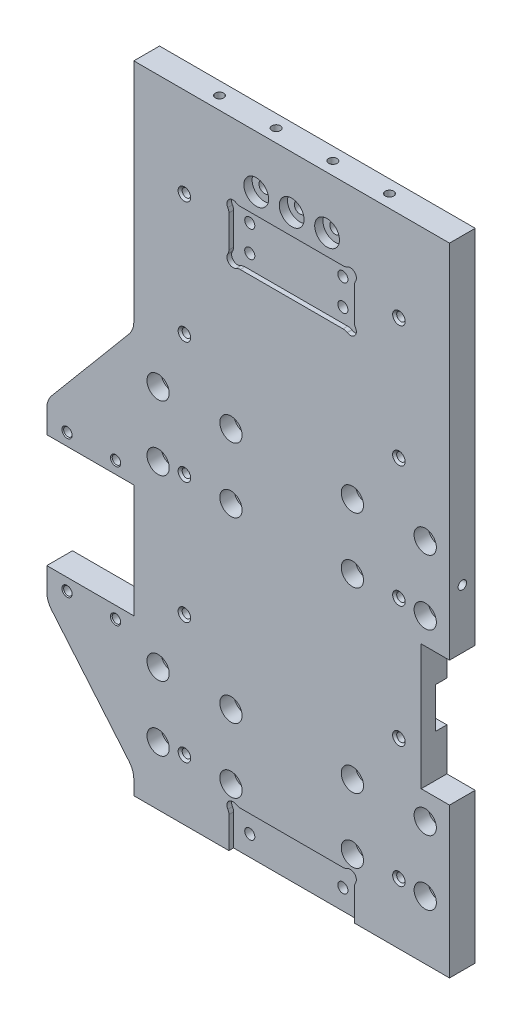
SolidWorks part; units mm, degrees
ref_plane "Front Plane" through (0, 0, 0) normal (0, 0, 1) x (1, 0, 0)
ref_plane "Top Plane" through (0, 0, 0) normal (0, 1, 0) x (1, 0, 0)
ref_plane "Right Plane" through (0, 0, 0) normal (1, 0, 0) x (0, 0, -1)
sketch "Sketch1" plane through (0, 0, 0) normal (0, 0, 1) x (1, 0, 0)
  line L0 (0, -105) -> (0, 209.5) construction
  line L1 (-78, 209.5) -> (78, 209.5)
  line L2 (-78, 209.5) -> (-78, -105)
  line L3 (-78, -105) -> (78, -105)
  line L4 (78, 209.5) -> (78, -105)
  line L5 (-78, 60) -> (78, 60) construction
  line L6 (-78, -60) -> (78, -60) construction
  line L7 (-78, 0) -> (78, 0) construction
  line L8 (30, -44) -> (66, -44) construction
  line L9 (30, -44) -> (30, -76) construction
  line L10 (30, -76) -> (66, -76) construction
  line L11 (66, -44) -> (66, -76) construction
  line L12 (30, -44) -> (66, -76) construction
  line L13 (30, -76) -> (66, -44) construction
  circle A0 centre (30, -44) radius 2.55
  circle A1 centre (66, -44) radius 2.55
  circle A2 centre (30, -76) radius 2.55
  circle A3 centre (66, -76) radius 2.55
  circle A4 centre (-66, -44) radius 2.55
  circle A5 centre (-66, -76) radius 2.55
  circle A6 centre (-30, -76) radius 2.55
  circle A7 centre (-30, -44) radius 2.55
  circle A8 centre (66, 76) radius 2.55
  circle A9 centre (66, 44) radius 2.55
  circle A10 centre (30, 76) radius 2.55
  circle A11 centre (30, 44) radius 2.55
  circle A12 centre (-30, 76) radius 2.55
  circle A13 centre (-30, 44) radius 2.55
  circle A14 centre (-66, 76) radius 2.55
  circle A15 centre (-66, 44) radius 2.55
  point P11 (48, -60)
  dimension "D3" = 5.1
  dimension "D1" = 120
  dimension "D2" = 30
  dimension "D4" = 36
  dimension "D5" = 32
  dimension "D6" = 48
  dimension "D7" = 45
  dimension "D8" = 314.5
extrude "Boss-Extrude1" add sketch "Sketch1" along normal blind 12.7
sketch "Sketch2" plane through (0, 0, 12.7) normal (0, 0, 1) x (1, 0, 0)
  circle A0 centre (-66, 76) radius 5.5
  circle A1 centre (-30, 76) radius 5.5
  circle A2 centre (-66, 44) radius 5.5
  circle A3 centre (-30, 44) radius 5.5
  circle A4 centre (30, 76) radius 5.5
  circle A5 centre (66, 76) radius 5.5
  circle A6 centre (30, 44) radius 5.5
  circle A7 centre (66, 44) radius 5.5
  circle A12 centre (-66, -44) radius 5.5
  circle A13 centre (-30, -44) radius 5.5
  circle A14 centre (-66, -76) radius 5.5
  circle A15 centre (-30, -76) radius 5.5
  circle A16 centre (30, -76) radius 5.5
  circle A17 centre (30, -44) radius 5.5
  circle A18 centre (66, -44) radius 5.5
  circle A19 centre (66, -76) radius 5.5
  dimension "D1" = 11
extrude "Cut-Extrude1" cut sketch "Sketch2" against normal blind 7
sketch "Sketch3" plane through (0, 0, 12.7) normal (0, 0, 1) x (1, 0, 0)
  line L0 (53, 209.5) -> (53, -105) construction
  line L1 (78, 209.5) -> (-78, 209.5) construction
  line L2 (-78, -105) -> (78, -105) construction
  line L3 (0, 209.5) -> (0, -105) construction
  point P8 (53, 165)
  point P9 (53, 105)
  point P11 (53, 45)
  point P12 (53, -15)
  point P13 (53, -75)
  point P14 (-53, -75)
  point P15 (-53, -15)
  point P16 (-53, 45)
  point P17 (-53, 105)
  point P18 (-53, 165)
  dimension "D1" = 53
  dimension "D2" = 30
  dimension "D4" = 60
  dimension "D3" = 5
hole_wizard "M5x0.8 Tapped Hole5" positions "3DSketch1" profile "Sketch4" tap size "M5x0.8" standard "ANSI Metric" end condition through all
sketch3d "3DSketch1"
  point P0 (53, 165, 12.7)
  point P3 (53, 105, 12.7)
  point P6 (53, 45, 12.7)
  point P9 (53, -15, 12.7)
  point P12 (53, -75, 12.7)
  point P15 (-53, 165, 12.7)
  point P18 (-53, 105, 12.7)
  point P21 (-53, 45, 12.7)
  point P24 (-53, -15, 12.7)
  point P27 (-53, -75, 12.7)
sketch "Sketch4" plane through (53, 165, 12.7) normal (1, 0, 0) x (0, -1, 0)
  line L0 (0, 0) -> (0, 12.7)
  line L1 (0, 12.7) -> (2.1, 12.7)
  line L2 (2.1, 12.7) -> (2.1, 0)
  line L5 (2.1, 0) -> (0, 0)
  line L11 (0, -6.35) -> (0, 107.95) construction
  dimension "Thru Tap Drill Dia." = 4.2
  dimension "Thru Tap Drill Depth" = 12.7
cosmetic thread "Hole Thread1" parameters "D2"=5
cosmetic thread "Hole Thread2" parameters "D2"=5
cosmetic thread "Hole Thread3" parameters "D2"=5
cosmetic thread "Hole Thread4" parameters "D2"=5
cosmetic thread "Hole Thread5" parameters "D2"=5
cosmetic thread "Hole Thread6" parameters "D2"=5
cosmetic thread "Hole Thread7" parameters "D2"=5
cosmetic thread "Hole Thread8" parameters "D2"=5
cosmetic thread "Hole Thread9" parameters "D2"=5
cosmetic thread "Hole Thread10" parameters "D2"=5
chamfer "Chamfer1" distance 1 angle 45 10 edges at (-50.9, 165, 12.7) (-50.9, 105, 12.7) (-50.9, 45, 12.7) (-50.9, -15, 12.7) (-50.9, -75, 12.7) (55.1, -75, 12.7) (55.1, -15, 12.7) (55.1, 45, 12.7) (55.1, 105, 12.7) (55.1, 165, 12.7)
sketch "Sketch5" plane through (0, 209.5, 0) normal (0, 1, 0) x (1, 0, 0)
  line L0 (0, 0) -> (0, -12.7) construction
  line L3 (78, -12.7) -> (-78, -12.7) construction
  line L5 (-42, -6.35) -> (42, -6.35) construction
  point P4 (14, -6.35)
  point P7 (0, -6.35)
  point P8 (-14, -6.35)
  dimension "D2" = 28
  dimension "D1" = 84
  dimension "D3" = 28
  dimension "D4" = 28
hole_wizard "M5x0.8 Tapped Hole3" positions "Sketch17" profile "Sketch18" tap size "M5x0.8" standard "ANSI Metric"
sketch "Sketch17" plane through (0, 209.5, 0) normal (0, 1, 0) x (1, 0, 0)
  point P0 (42, -6.35)
  point P3 (14, -6.35)
  point P6 (-14, -6.35)
  point P9 (-42, -6.35)
sketch "Sketch18" plane through (42, 209.5, 6.35) normal (1, 0, 0) x (0, 0, 1)
  line L0 (0, 0) -> (0, 21.6618)
  line L1 (0, 21.6618) -> (2.1, 20.4)
  line L2 (2.1, 20.4) -> (2.1, 0)
  line L5 (2.1, 0) -> (0, 0)
  line L10 (0, 21.6618) -> (-2.1, 20.4) construction
  line L11 (0, -6.35) -> (0, 107.95) construction
  dimension "Tap Drill Dia." = 4.2
  dimension "Tap Drill Depth" = 20.4
  dimension "Drill Angle" = 118
cosmetic thread "Hole Thread28" parameters "D1"=18, "D2"=5
cosmetic thread "Hole Thread29" parameters "D1"=18, "D2"=5
cosmetic thread "Hole Thread30" parameters "D1"=18, "D2"=5
cosmetic thread "Hole Thread31" parameters "D1"=18, "D2"=5
sketch "Sketch7" plane through (0, 0, 12.7) normal (0, 0, 1) x (1, 0, 0)
  line L0 (-78, -95) -> (78, -95) construction
  line L1 (0, 209.5) -> (0, -105) construction
  line L2 (78, -105) -> (78, 209.5) construction
  line L3 (0, 209.5) -> (0, -105) construction
  line L4 (-78, -105) -> (78, -105) construction
  circle A1 centre (-23, -95) radius 2.5 construction
  circle A2 centre (23, -95) radius 2.5 construction
  point P4 (0, -95)
  point P7 (-23, -95)
  point P11 (23, -95)
  dimension "D1" = 46
  dimension "D2" = 5
  dimension "D3" = 10
sketch "Sketch8" plane through (0, 0, 0) normal (0, 0, -1) x (-1, 0, 0)
  line L0 (-53, 45) -> (-53, -15) construction
  line L1 (-30, 44) -> (-30, -44) construction
  line L3 (-78, -105) -> (-78, 209.5) construction
  line L4 (-78, 31) -> (-64, 31)
  line L5 (-78, 31) -> (-78, -31)
  line L6 (-78, -31) -> (-64, -31)
  line L7 (-64, 31) -> (-64, -31)
  line L8 (-71, -31) -> (-71, 31) construction
  line L9 (-78, 0) -> (-64, 0) construction
  point P9 (-30, 0)
  point P221 (-71, 0)
  dimension "D1" = 62
  dimension "D2" = 11
extrude "Cut-Extrude3" cut sketch "Sketch8" against normal through all
sketch "Sketch9" plane through (0, 0, 0) normal (0, 0, -1) x (-1, 0, 0)
  line L0 (-30, 44) -> (-30, -44) construction
  line L1 (-78, 0) -> (78, 0)
  line L2 (-78, 31) -> (-78, 209.5) construction
  line L3 (78, 209.5) -> (78, -105) construction
  point P7 (-30, 0)
extrude "Cut-Extrude-Thin1" cut sketch "Sketch9" against normal blind 5.5 thin thin type mid plane wall 20
sketch "Sketch10" plane through (0, 0, 12.7) normal (0, 0, 1) x (1, 0, 0)
  line L0 (-30, 44) -> (-30, -44) construction
  line L1 (-30, 0) -> (-99, 0) construction
  line L2 (-78, 209.5) -> (-78, -105) construction
  line L3 (-111, -20) -> (-87, -20) construction
  line L4 (-111, -20) -> (-111, 20) construction
  line L5 (-111, 20) -> (-87, 20) construction
  line L6 (-87, -20) -> (-87, 20) construction
  line L7 (-99, 20) -> (-99, -20) construction
  line L8 (-111, 0) -> (-87, 0) construction
  line L9 (-121, 28) -> (-121, 43)
  line L10 (-78, 28) -> (-78, 94.2454)
  line L11 (-78, 28) -> (-121, 28)
  line L12 (-79, 28) -> (-119, 28) construction
  line L13 (-79, -27) -> (-119, -27) construction
  line L14 (-79, -27) -> (-79, 27) construction
  line L15 (-79, 27) -> (-119, 27) construction
  line L16 (-119, -27) -> (-119, 27) construction
  line L17 (-99, 27) -> (-99, -27) construction
  line L18 (-79, 0) -> (-119, 0) construction
  line L19 (-121, 43) -> (-78, 94.2454)
  line L20 (-78, -28) -> (-78, -94.2454)
  line L21 (-121, -43) -> (-78, -94.2454)
  line L22 (-121, -28) -> (-121, -43)
  line L23 (-78, -28) -> (-121, -28)
  circle A0 centre (-111, 34) radius 2.1
  circle A1 centre (-87, 34) radius 2.1
  circle A2 centre (-87, -34) radius 2.1
  circle A3 centre (-111, -34) radius 2.1
  dimension "D10" = 4.2
  dimension "D11" = 6
  dimension "D1" = 40
  dimension "D2" = 24
  dimension "D3" = 21
  dimension "D5" = 54
  dimension "D6" = 40
  dimension "D8" = 140
  dimension "D4" = 15
  dimension "D9" = 2
  dimension "D7" = 1
extrude "Boss-Extrude2" add sketch "Sketch10" against normal up to surface (12.7 mm away) up to face at (-63.45, 44, 0)
cosmetic thread "Hole Thread17" parameters "D2"=5
cosmetic thread "Hole Thread18" parameters "D2"=5
cosmetic thread "Hole Thread19" parameters "D2"=5
cosmetic thread "Hole Thread20" parameters "D2"=5
fillet "Fillet1" radius 10 4 edges at (-121, 43, 6.35) (-121, -43, 6.35) (-78, -94.2454, 6.35) (-78, 94.2454, 6.35)
hole_wizard "M5x0.8 Tapped Hole2" positions "Sketch11" profile "Sketch12" tap size "M5x0.8" standard "ANSI Metric" end condition through all
sketch "Sketch11" plane through (0, 0, 12.7) normal (0, 0, 1) x (1, 0, 0)
  point P0 (-87, 34)
  point P3 (-111, 34)
  point P6 (-87, -34)
  point P9 (-111, -34)
sketch "Sketch12" plane through (-87, 34, 12.7) normal (1, 0, 0) x (0, -1, 0)
  line L0 (0, 0) -> (0, 12.7)
  line L1 (0, 12.7) -> (2.1, 12.7)
  line L2 (2.1, 12.7) -> (2.1, 0.425)
  line L3 (2.1, 0.425) -> (2.525, 0)
  line L5 (2.525, 0) -> (0, 0)
  line L6 (-2.1, 0.425) -> (-2.525, 0) construction
  line L11 (0, -6.35) -> (0, 107.95) construction
  dimension "Thru Tap Drill Dia." = 4.2
  dimension "Thru Tap Drill Depth" = 12.7
  dimension "Near C'Sink Dia." = 5.05
  dimension "Near C'Sink Angle" = 90
sketch "Sketch13" plane through (0, 0, 12.7) normal (0, 0, 1) x (1, 0, 0)
  line L0 (0, 209.5) -> (0, 166.5) construction
  line L1 (78, 209.5) -> (-78, 209.5) construction
  line L3 (-23, 153.5) -> (23, 153.5) construction
  line L4 (-23, 153.5) -> (-23, 166.5) construction
  line L5 (-23, 166.5) -> (23, 166.5) construction
  line L6 (23, 153.5) -> (23, 166.5) construction
  line L7 (0, 166.5) -> (0, 153.5) construction
  line L8 (-23, 160) -> (23, 160) construction
  point P5 (0, 160)
  dimension "D1" = 43
  dimension "D2" = 13
  dimension "D3" = 46
hole_wizard "M6x1.0 Tapped Hole2" positions "Sketch14" profile "Sketch15" tap size "M6x1.0" standard "ANSI Metric" end condition through all
sketch "Sketch14" plane through (0, 0, 12.7) normal (0, 0, 1) x (1, 0, 0)
  point P0 (-23, 166.5)
  point P3 (23, 166.5)
  point P6 (-23, 153.5)
  point P9 (23, 153.5)
  point P13 (-23, -95)
  point P16 (23, -95)
sketch "Sketch15" plane through (-23, 166.5, 12.7) normal (1, 0, 0) x (0, -1, 0)
  line L0 (0, 0) -> (0, 12.7)
  line L1 (0, 12.7) -> (2.5, 12.7)
  line L2 (2.5, 12.7) -> (2.5, 0.525)
  line L3 (2.5, 0.525) -> (3.025, 0)
  line L5 (3.025, 0) -> (0, 0)
  line L6 (-2.5, 0.525) -> (-3.025, 0) construction
  line L11 (0, -6.35) -> (0, 107.95) construction
  dimension "Thru Tap Drill Dia." = 5
  dimension "Thru Tap Drill Depth" = 12.7
  dimension "Near C'Sink Dia." = 6.05
  dimension "Near C'Sink Angle" = 90
cosmetic thread "Hole Thread21" parameters "D2"=6
cosmetic thread "Hole Thread22" parameters "D2"=6
cosmetic thread "Hole Thread23" parameters "D2"=6
cosmetic thread "Hole Thread24" parameters "D2"=6
cosmetic thread "Hole Thread25" parameters "D2"=6
cosmetic thread "Hole Thread26" parameters "D2"=6
sketch "Sketch16" plane through (0, 0, 12.7) normal (0, 0, 1) x (1, 0, 0)
  line L0 (23, 166.5) -> (-23, 153.5) construction
  line L1 (-23, -95) -> (23, -95) construction
  line L2 (-31, 146.5) -> (31, 146.5)
  line L3 (-31, 146.5) -> (-31, 173.5)
  line L4 (-31, 173.5) -> (31, 173.5)
  line L5 (31, 146.5) -> (31, 173.5)
  line L6 (0, 173.5) -> (0, 146.5) construction
  line L7 (-31, 160) -> (31, 160) construction
  line L9 (-31, -84) -> (31, -84)
  line L10 (-31, -84) -> (-31, -106)
  line L11 (-31, -106) -> (31, -106)
  line L12 (31, -84) -> (31, -106)
  line L13 (0, -106) -> (0, -84) construction
  line L14 (-31, -95) -> (31, -95) construction
  point P4 (0, 160)
  point P10 (0, -95)
  dimension "D1" = 62
  dimension "D2" = 27
  dimension "D3" = 22
  dimension "D4" = 62
extrude "Cut-Extrude4" cut sketch "Sketch16" against normal blind 2.3
sketch "Sketch19" plane through (0, 0, 0) normal (0, 0, -1) x (-1, 0, 0)
  line L0 (0, 209.5) -> (0, 183.65) construction
  line L1 (-78, 209.5) -> (78, 209.5) construction
  line L2 (-17.5, 183.65) -> (17.5, 183.65) construction
  point P8 (0, 183.65)
  dimension "D1" = 25.85
  dimension "D2" = 35
hole_wizard "CBORE for M5 Hex Head Bolt1" positions "Sketch20" profile "Sketch22" counterbore size "M5" standard "ANSI Metric" end condition through all
sketch "Sketch20" plane through (0, 0, 12.7) normal (0, 0, 1) x (1, 0, 0)
  point P0 (-17.5, 183.65)
  point P3 (0, 183.65)
  point P6 (17.5, 183.65)
sketch "Sketch22" plane through (-17.5, 183.65, 12.7) normal (1, 0, 0) x (0, -1, 0)
  line L0 (0, 0) -> (0, 12.7)
  line L1 (0, 12.7) -> (2.75, 12.7)
  line L3 (2.75, 12.7) -> (2.75, 4.08)
  line L4 (2.75, 4.08) -> (6.12, 4.08)
  line L5 (6.12, 4.08) -> (6.12, 0)
  line L7 (6.12, 0) -> (0, 0)
  line L11 (0, -6.35) -> (0, 107.95) construction
  dimension "Thru Hole Dia." = 5.5
  dimension "Thru Hole Depth" = 12.7
  dimension "C'Bore Dia." = 12.24
  dimension "C'Bore Depth" = 4.08
sketch "Sketch23" plane through (0, 0, 0) normal (0, 0, -1) x (-1, 0, 0)
  point P0 (-66, 76)
  point P1 (-66, 44)
sketch "Sketch24" plane through (78, 0, 0) normal (1, 0, 0) x (0, 0, -1)
  line L0 (0, 76) -> (-12.7, 76) construction
  line L1 (-12.7, 31) -> (-12.7, 209.5) construction
  line L2 (0, 44) -> (-12.7, 44) construction
  line L3 (-6.35, 76) -> (-6.35, 44) construction
  circle A0 centre (-6.35, 60) radius 2.5 construction
  dimension "D1" = 5
hole_wizard "M5x0.8 Tapped Hole4" positions "Sketch25" profile "Sketch26" tap size "M5x0.8" standard "ANSI Metric"
sketch "Sketch25" plane through (78, 0, 0) normal (1, 0, 0) x (0, 0, -1)
  point P0 (-6.35, 60)
sketch "Sketch26" plane through (78, 60, 6.35) normal (0, 1, 0) x (0, 0, -1)
  line L0 (0, 0) -> (0, 25.2618)
  line L1 (0, 25.2618) -> (2.1, 24)
  line L2 (2.1, 24) -> (2.1, 0)
  line L5 (2.1, 0) -> (0, 0)
  line L10 (0, 25.2618) -> (-2.1, 24) construction
  line L11 (0, -6.35) -> (0, 107.95) construction
  dimension "Tap Drill Dia." = 4.2
  dimension "Tap Drill Depth" = 24
  dimension "Drill Angle" = 118
cosmetic thread "Hole Thread32" parameters "D1"=20, "D2"=5
sketch "Sketch27" plane through (0, 0, 10.4) normal (0, 0, 1) x (1, 0, 0)
  line L4 (-31.1, 173.6) -> (-28.0104, 170.5104) construction
  line L5 (0, 173.6) -> (0, 146.4) construction
  line L6 (-31.1, 160) -> (31.1, 160) construction
  line L8 (31.1, 146.4) -> (31.1, 173.6)
  line L9 (31.1, 173.6) -> (-31.1, 173.6)
  line L10 (-31.1, 173.6) -> (-31.1, 146.4)
  line L11 (-31.1, 146.4) -> (31.1, 146.4)
  line L12 (31.1, 146.4) -> (31.1, 173.6) construction
  line L13 (31.1, 173.6) -> (-31.1, 173.6) construction
  line L14 (-31.1, 173.6) -> (-31.1, 146.4) construction
  line L15 (-31.1, 146.4) -> (31.1, 146.4) construction
  line L19 (-31.1, -83.9) -> (-27.1012, -87.8988) construction
  line L20 (0, -83.9) -> (0, -105.1) construction
  line L23 (-31.1, -105.1) -> (31.1, -105.1)
  line L24 (31.1, -105.1) -> (31.1, -83.9)
  line L25 (31.1, -83.9) -> (-31.1, -83.9)
  line L26 (-31.1, -83.9) -> (-31.1, -105.1)
  line L27 (-31.1, -105.1) -> (31.1, -105.1) construction
  line L28 (31.1, -105.1) -> (31.1, -83.9) construction
  line L29 (31.1, -83.9) -> (-31.1, -83.9) construction
  line L30 (-31.1, -83.9) -> (-31.1, -105.1) construction
  circle A0 centre (-28.9787, 171.4787) radius 3
  circle A1 centre (28.9787, 171.4787) radius 3
  circle A2 centre (28.9787, 148.5213) radius 3
  circle A3 centre (-28.9787, 148.5213) radius 3
  circle A4 centre (-28.9787, -86.0213) radius 3
  circle A5 centre (28.9787, -86.0213) radius 3
  dimension "D3" = 6
  dimension "D2" = 45
  dimension "D4" = 0.1
  dimension "D5" = 45
  dimension "D1" = 0.1
extrude "Cut-Extrude5" cut sketch "Sketch27" along normal up to surface (2.3 mm away) up to face at (-11.38, 183.65, 12.7)
fillet "Fillet2" radius 4 12 edges at (31, -88.2381, 11.55) (26.7619, -84, 11.55) (-26.7619, -84, 11.55) (-31, -88.2381, 11.55) (-31, 150.7381, 11.55) (-26.7619, 146.5, 11.55) (26.7619, 146.5, 11.55) (31, 150.7381, 11.55) (31, 169.2619, 11.55) (26.7619, 173.5, 11.55) (-26.7619, 173.5, 11.55) (-31, 169.2619, 11.55)
